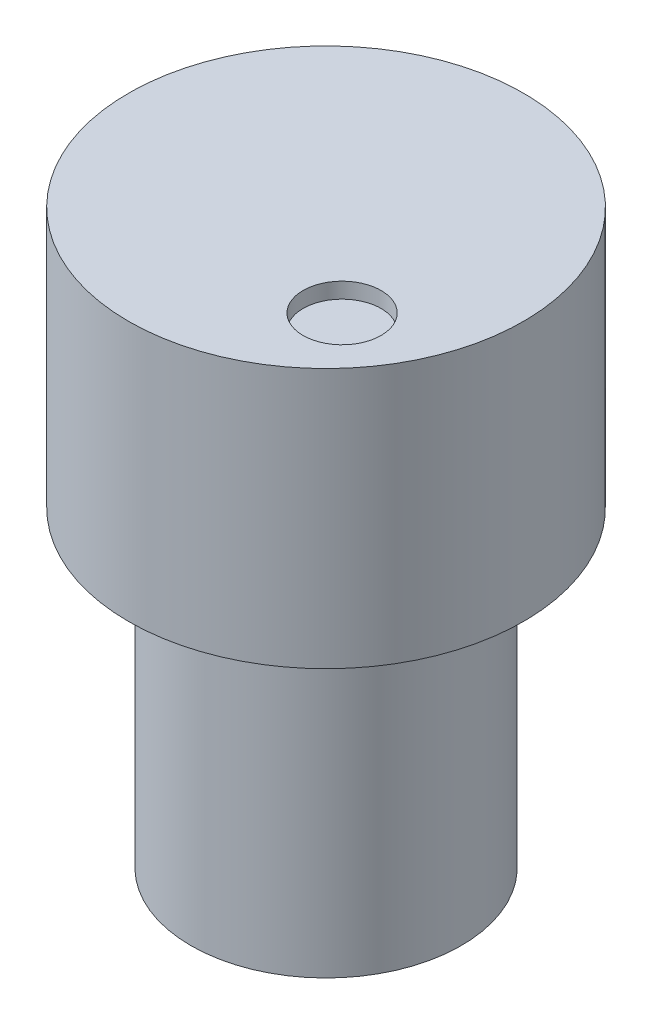
SolidWorks part; units mm, degrees
ref_plane "Front Plane" through (0, 0, 0) normal (0, 0, 1) x (1, 0, 0)
ref_plane "Top Plane" through (0, 0, 0) normal (0, 1, 0) x (1, 0, 0)
ref_plane "Right Plane" through (0, 0, 0) normal (1, 0, 0) x (0, 0, -1)
sketch "Sketch1" plane through (0, 0, 0) normal (0, 1, 0) x (1, 0, 0)
  circle A0 centre (0, 0) radius 3.2
  circle A1 centre (0, 0) radius 5.2
  dimension "D1" = 6.4
  dimension "D2" = 2
extrude "Boss-Extrude1" add sketch "Sketch1" along normal blind 12
sketch "Sketch2" plane through (0, 12, 0) normal (0, 1, 0) x (1, 0, 0)
  circle A0 centre (0, 0) radius 7.6
  dimension "D1" = 15.2
extrude "Boss-Extrude2" add sketch "Sketch2" along normal blind 10
sketch "Sketch4" plane through (0, 12, 0) normal (0, -1, 0) x (1, 0, 0)
  line L0 (-2.6458, -1.8) -> (2.6458, -1.8)
  circle A1 centre (0, 0) radius 3.2
  circle A2 centre (0, 0) radius 3.2
  circle A3 centre (0, 0) radius 3.2 construction
  point P7 (0, 3.4)
  circle M5 centre (0, 0) radius 3.2
  dimension "D2" = 5.2
  dimension "D1" = 0
extrude "Boss-Extrude4" add sketch "Sketch4" along normal blind 5 contours L0 M5
sketch "Sketch5" plane through (0, 22, 0) normal (0, 1, 0) x (1, 0, 0)
  line L0 (-2.6458, 1.8) -> (2.6458, 1.8) construction
  line L1 (-2.6458, 1.8) -> (2.6458, 1.8) construction
  line L2 (0, 1.8) -> (0, -7.6) construction
  line L3 (3.8302, -3.2139) -> (0, 0) construction
  circle A0 centre (3.8302, -3.2139) radius 1.5
  circle A1 centre (0, 0) radius 7.6 construction
  dimension "D3" = 3
  dimension "D1" = 310
  dimension "D2" = 5
extrude "Cut-Extrude1" cut sketch "Sketch5" against normal blind 0.6
